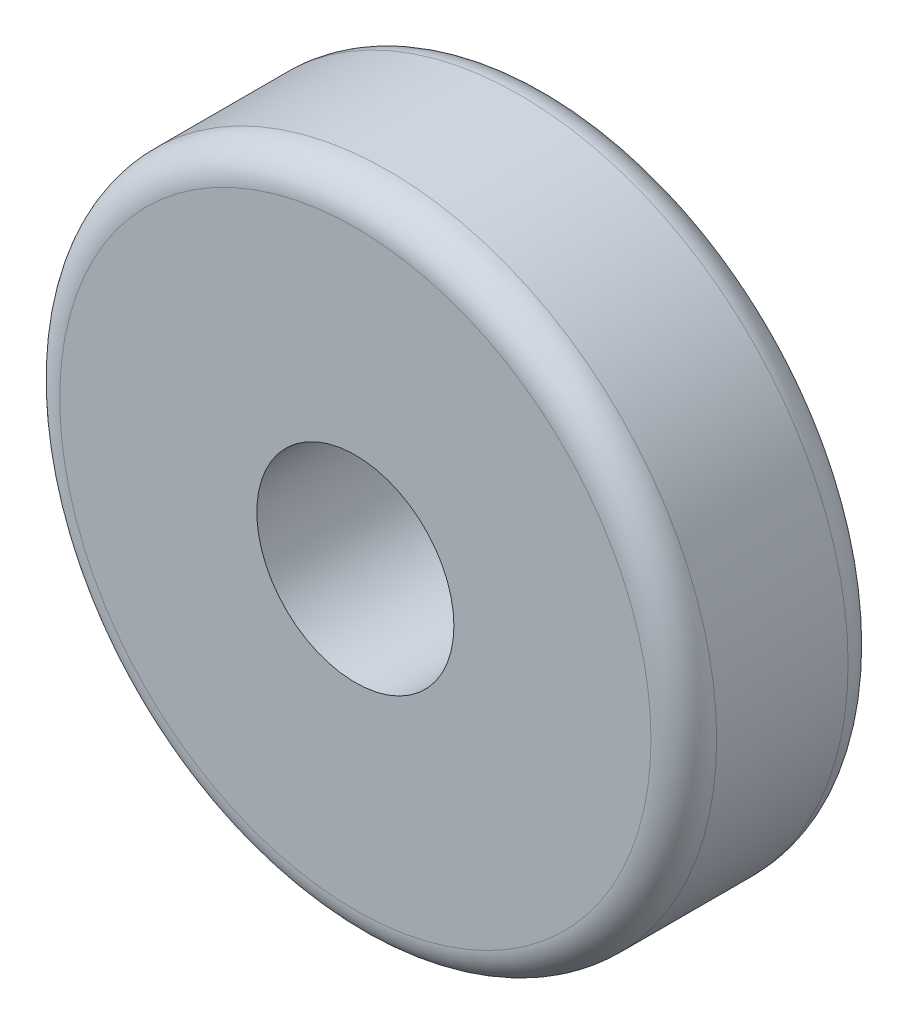
SolidWorks part; units mm, degrees
ref_plane "前视基准面" through (0, 0, 0) normal (0, 0, 1) x (1, 0, 0)
ref_plane "上视基准面" through (0, 0, 0) normal (0, 1, 0) x (1, 0, 0)
ref_plane "右视基准面" through (0, 0, 0) normal (1, 0, 0) x (0, 0, -1)
other "Configuration Table"
sketch "草图1" plane through (0, 0, 0) normal (0, 0, 1) x (1, 0, 0)
  circle A0 centre (0, 0) radius 10
  circle A1 centre (0, 0) radius 3
  dimension "D1" = 6
  dimension "D2" = 20
extrude "凸台-拉伸1" add sketch "草图1" along normal blind 6
fillet "圆角1" radius 1 2 edges at (10, 0, 0) (10, 0, 6)
